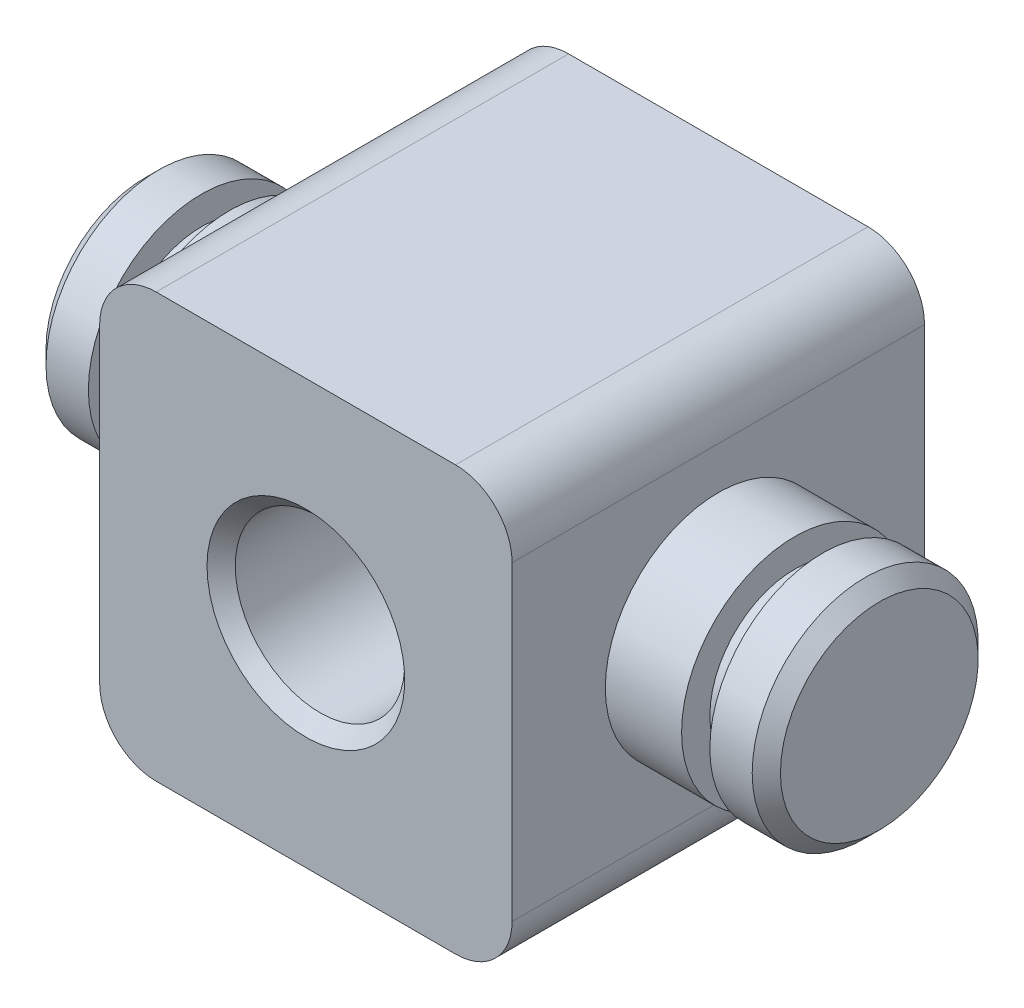
SolidWorks part; units mm, degrees
ref_plane "Front Plane" through (0, 0, 0) normal (0, 0, 1) x (1, 0, 0)
ref_plane "Top Plane" through (0, 0, 0) normal (0, 1, 0) x (1, 0, 0)
ref_plane "Right Plane" through (0, 0, 0) normal (1, 0, 0) x (0, 0, -1)
sketch "Sketch1" plane through (0, 0, 0) normal (0, 0, 1) x (1, 0, 0)
  line L1 (-5.3, 7.5) -> (5.3, 7.5)
  line L2 (-7.3, 5.5) -> (-7.3, -5.5)
  line L3 (-5.3, -7.5) -> (5.3, -7.5)
  line L4 (7.3, 5.5) -> (7.3, -5.5)
  line L5 (-7.3, 7.5) -> (7.3, -7.5) construction
  line L6 (-7.3, -7.5) -> (7.3, 7.5) construction
  circle A0 centre (0, 0) radius 3
  arc A1 (5.3, 7.5) -> (7.3, 5.5) centre (5.3, 5.5) cw
  arc A2 (-7.3, -5.5) -> (-5.3, -7.5) centre (-5.3, -5.5) ccw
  arc A3 (-5.3, 7.5) -> (-7.3, 5.5) centre (-5.3, 5.5) ccw
  arc A4 (5.3, -7.5) -> (7.3, -5.5) centre (5.3, -5.5) ccw
  point P0 (0, 0)
  dimension "D3" = 6
  dimension "D4" = 2
  dimension "D1" = 14.6
  dimension "D2" = 15
extrude "Boss-Extrude1" add sketch "Sketch1" along normal mid plane 14.6
sketch "Sketch2" plane through (0, 0, 0) normal (0, 0, 1) x (1, 0, 0)
  line L0 (-27.281, 0) -> (27.281, 0) construction
  line L1 (7.3, 0) -> (7.3, 4)
  line L2 (7.3, 4) -> (10, 4)
  line L3 (10, 4) -> (10, 3)
  line L4 (10, 3) -> (11, 3)
  line L5 (11, 3) -> (11, 4)
  line L6 (11, 4) -> (12.5, 4)
  line L7 (13, 3.5) -> (13, 0)
  line L8 (13, 0) -> (7.3, 0)
  line L9 (12.5, 4) -> (13, 3.5)
  line L10 (0, 0) -> (0, 4.8113) construction
  line L11 (-12.5, 4) -> (-13, 3.5)
  line L12 (-13, 0) -> (-7.3, 0)
  line L13 (-13, 3.5) -> (-13, 0)
  line L14 (-11, 4) -> (-12.5, 4)
  line L15 (-11, 3) -> (-11, 4)
  line L16 (-10, 3) -> (-11, 3)
  line L17 (-10, 4) -> (-10, 3)
  line L18 (-7.3, 4) -> (-10, 4)
  line L19 (-7.3, 0) -> (-7.3, 4)
  line L20 (-7.3, 5.5) -> (-7.3, -5.5) construction
  point P9 (13, 4)
  point P23 (-13, 4)
  dimension "D1" = 4
  dimension "D2" = 3
  dimension "D3" = 4
  dimension "D4" = 1
  dimension "D5" = 5.7
  dimension "D6" = 2
  dimension "D7" = 0.5
  dimension "D8" = 45
revolve "Revolve1" add sketch "Sketch2" angle 360 about L0
chamfer "Chamfer1" distance 0.5 angle 45 2 edges at (3, 0, -7.3) (3, 0, 7.3)
